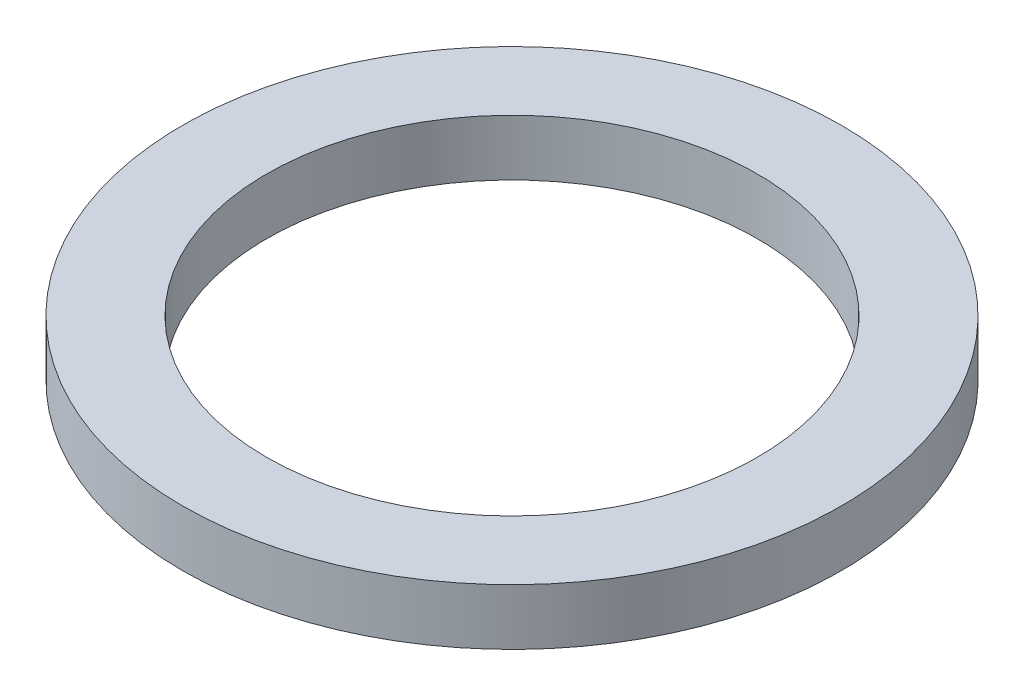
SolidWorks part; units mm, degrees
ref_plane "Спереди" through (0, 0, 0) normal (0, 0, 1) x (1, 0, 0)
ref_plane "Сверху" through (0, 0, 0) normal (0, 1, 0) x (1, 0, 0)
ref_plane "Справа" through (0, 0, 0) normal (1, 0, 0) x (0, 0, -1)
sketch "Эскиз1" plane through (0, 0, 0) normal (0, 1, 0) x (1, 0, 0)
  circle A0 centre (0, 0) radius 17.5
  circle A1 centre (0, 0) radius 23.5
  dimension "D1" = 47
  dimension "D2" = 35
extrude "тело" add sketch "Эскиз1" along normal blind 4
